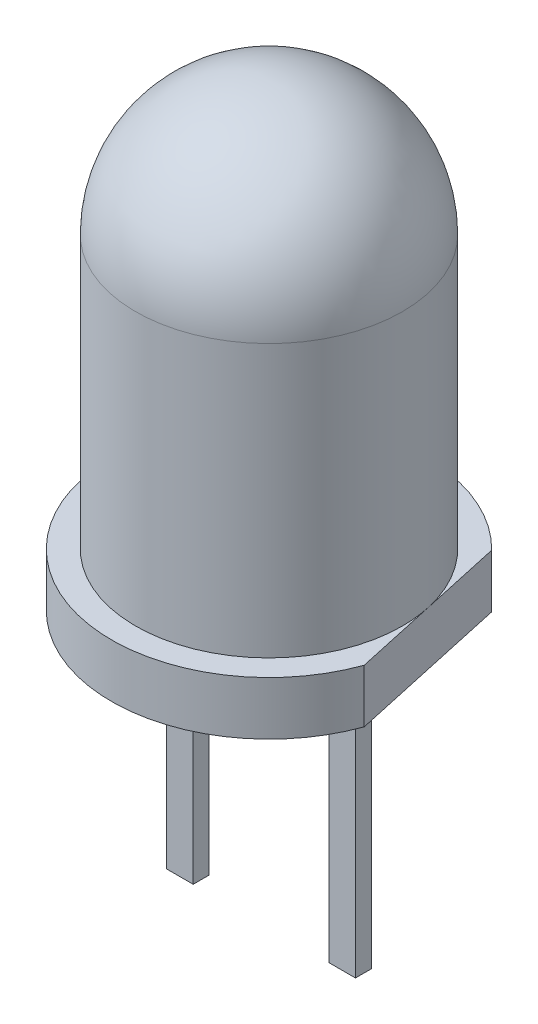
SolidWorks part; units mm, degrees
ref_plane "Front Plane" through (0, 0, 0) normal (0, 0, 1) x (1, 0, 0)
ref_plane "Top Plane" through (0, 0, 0) normal (0, 1, 0) x (1, 0, 0)
ref_plane "Right Plane" through (0, 0, 0) normal (1, 0, 0) x (0, 0, -1)
sketch "Sketch1" plane through (0, 0, 0) normal (0, 0, 1) x (1, 0, 0)
  line L0 (0, -170.0139) -> (0, 8330.6815) construction
  line L1 (2.5, 4.0232) -> (2.5, -1.0768)
  line L2 (2.5, -1.0768) -> (0, -1.0768)
  line L3 (0, 6.5232) -> (0, -1.0768)
  arc A0 (0, 6.5232) -> (2.5, 4.0232) centre (0, 4.0232) cw
  dimension "D1" = 2.5
  dimension "D2" = 7.6
revolve "Revolve1" add sketch "Sketch1" angle 360 about L0
sketch "Sketch2" plane through (0, -1.0768, 0) normal (0, -1, 0) x (1, 0, 0)
  line L0 (2.1059, -2.0659) -> (2.7777, 0.9933)
  arc A0 (2.7777, 0.9933) -> (2.1059, -2.0659) centre (0, 0) ccw
  circle A1 centre (0, 0) radius 2.5 construction
  dimension "D1" = 2.95
extrude "Boss-Extrude1" add sketch "Sketch2" along normal blind 1
sketch "Sketch4" plane through (0, 0, 0) normal (0, 0, 1) x (1, 0, 0)
  line L0 (-2.95, -2.0768) -> (2.7777, -2.0768) construction
  line L2 (1.27, -2.0768) -> (1.77, -2.0768)
  line L3 (1.27, -2.0768) -> (1.27, -7.0768)
  line L4 (1.27, -7.0768) -> (1.77, -7.0768)
  line L5 (1.77, -2.0768) -> (1.77, -7.0768)
  line L6 (-1.77, -2.0768) -> (-1.77, -7.0768)
  line L7 (-1.27, -7.0768) -> (-1.77, -7.0768)
  line L8 (-1.27, -2.0768) -> (-1.27, -7.0768)
  line L9 (-1.27, -2.0768) -> (-1.77, -2.0768)
  line L25 (0, -1000) -> (0, 49000) construction
  dimension "D1" = 1.27
  dimension "D2" = 0.5
  dimension "D4" = 5
extrude "Boss-Extrude2" add sketch "Sketch4" along normal mid plane 0.3
